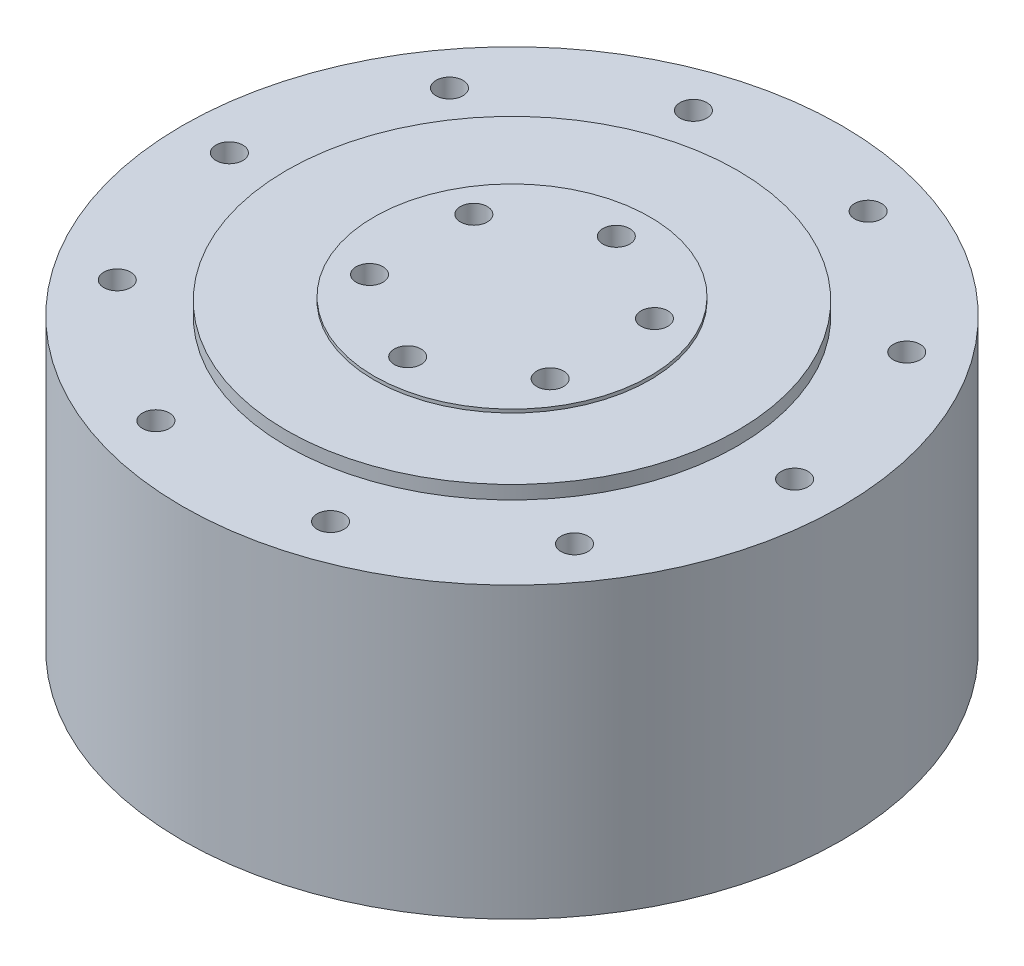
SolidWorks part; units mm, degrees
ref_plane "前基準面" through (0, 0, 0) normal (0, 0, 1) x (1, 0, 0)
ref_plane "上基準面" through (0, 0, 0) normal (0, 1, 0) x (1, 0, 0)
ref_plane "右基準面" through (0, 0, 0) normal (1, 0, 0) x (0, 0, -1)
sketch "草圖1" plane through (0, 0, 0) normal (0, 1, 0) x (1, 0, 0)
  circle A0 centre (0, 0) radius 49
  dimension "D1" = 98
extrude "填料-伸長1" add sketch "草圖1" along normal blind 43
sketch "草圖2" plane through (0, 43, 0) normal (0, 1, 0) x (1, 0, 0)
  circle A0 centre (0, 0) radius 33.5
  dimension "D1" = 67
extrude "填料-伸長2" add sketch "草圖2" along normal blind 2
sketch "草圖4" plane through (0, 45, 0) normal (0, 1, 0) x (1, 0, 0)
  circle A0 centre (0, 0) radius 20.5
  dimension "D1" = 41
extrude "填料-伸長4" add sketch "草圖4" along normal blind 0.5
sketch "草圖5" plane through (0, 45.5, 0) normal (0, 1, 0) x (1, 0, 0)
  line L0 (0, 0) -> (50000, 0) construction
  line L1 (0, 0) -> (0, 50000) construction
  circle A1 centre (0, 15.5) radius 2
  dimension "D1" = 4
  dimension "D2" = 15.5
extrude "除料-伸長1" cut sketch "草圖5" against normal blind 5
pattern_circular "環狀複製排列1" count 6 over 360 about axis through (0, 0, 0) along (0, 1, 0) of "除料-伸長1"
sketch "草圖6" plane through (0, 43, 0) normal (0, 1, 0) x (1, 0, 0)
  line L0 (0, 0) -> (50000, 0) construction
  line L1 (0, 0) -> (0, 50000) construction
  circle A1 centre (-42, 0) radius 2
  dimension "D1" = 4
  dimension "D2" = 42
extrude "除料-伸長2" cut sketch "草圖6" against normal blind 5
pattern_circular "環狀複製排列2" count 10 over 360 about axis through (0, 0, 0) along (0, 1, 0) of "除料-伸長2"
sketch "草圖7" plane through (0, 0, 0) normal (0, -1, 0) x (1, 0, 0)
  line L0 (0, 0) -> (50000, 0) construction
  line L1 (0, 0) -> (0, 50000) construction
  circle A0 centre (42, 0) radius 2
  dimension "D1" = 4
  dimension "D2" = 42
extrude "除料-伸長3" cut sketch "草圖7" against normal blind 5
pattern_circular "環狀複製排列3" count 10 over 360 about axis through (0, 0, 0) along (0, 1, 0) of "除料-伸長3"
